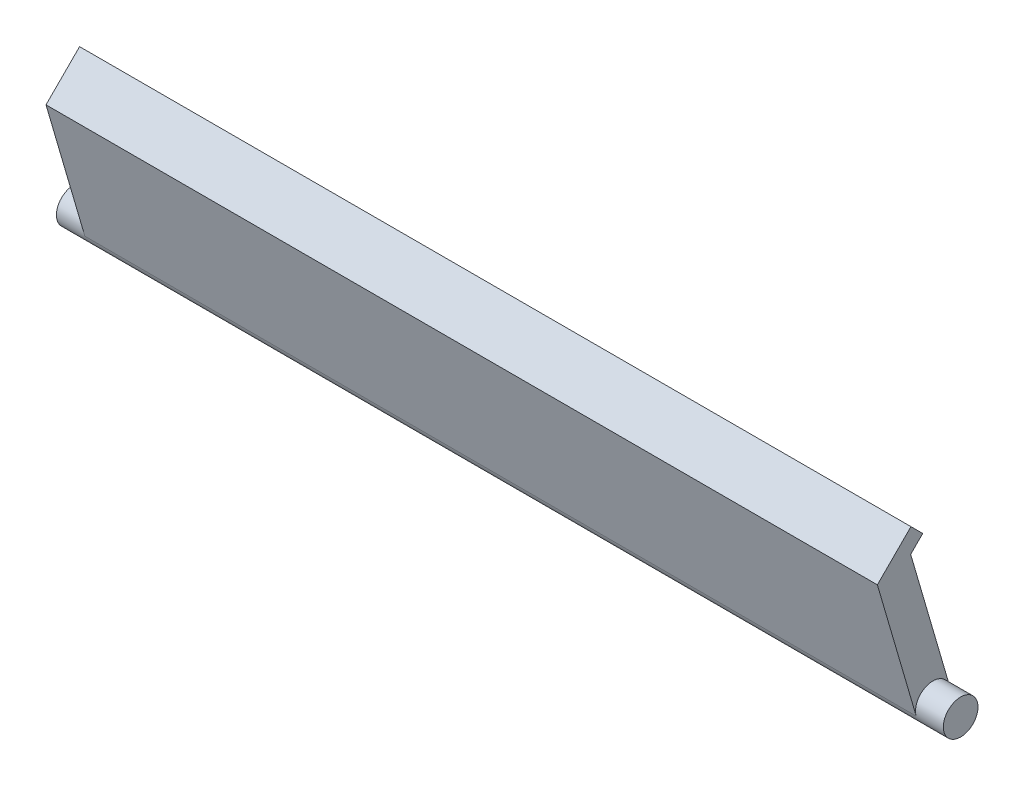
SolidWorks part; units mm, degrees
ref_plane "Front Plane" through (0, 0, 0) normal (0, 0, 1) x (1, 0, 0)
ref_plane "Top Plane" through (0, 0, 0) normal (0, 1, 0) x (1, 0, 0)
ref_plane "Right Plane" through (0, 0, 0) normal (1, 0, 0) x (0, 0, -1)
sketch "Sketch1" plane through (0, 0, 0) normal (1, 0, 0) x (0, 0, -1)
  circle A0 centre (0, 0) radius 25
  dimension "D1" = 50
extrude "Boss-Extrude1" add sketch "Sketch1" along normal blind 1200
sketch "Sketch2" plane through (1200, 0, 0) normal (1, 0, 0) x (0, 0, -1)
  line L2 (-32.0105, 198.9983) -> (23.9996, 7.0013)
  line L3 (-80.0097, 184.9958) -> (-23.9996, -7.0013)
  line L4 (-32.0105, 198.9983) -> (-14.6181, 216.3907)
  line L5 (-80.0097, 184.9958) -> (-31.6165, 233.389)
  line L6 (-31.6165, 233.389) -> (-14.6181, 216.3907)
  circle A0 centre (0, 0) radius 25 construction
  arc A1 (23.9996, 7.0013) -> (-23.9996, -7.0013) centre (0, 0) ccw
  point P6 (-56.0101, 191.9971)
  circle M5 centre (0, 0) radius 25
  dimension "D2" = 50
extrude "Boss-Extrude2" add sketch "Sketch2" against normal blind 1198 contours L6 L5 L3 L2 L4 M5
sketch "Sketch3" plane through (1200, 0, 0) normal (1, 0, 0) x (0, 0, -1)
  circle A0 centre (0, 0) radius 25
extrude "Boss-Extrude3" add sketch "Sketch3" along normal blind 40 and the other way blind 1238
